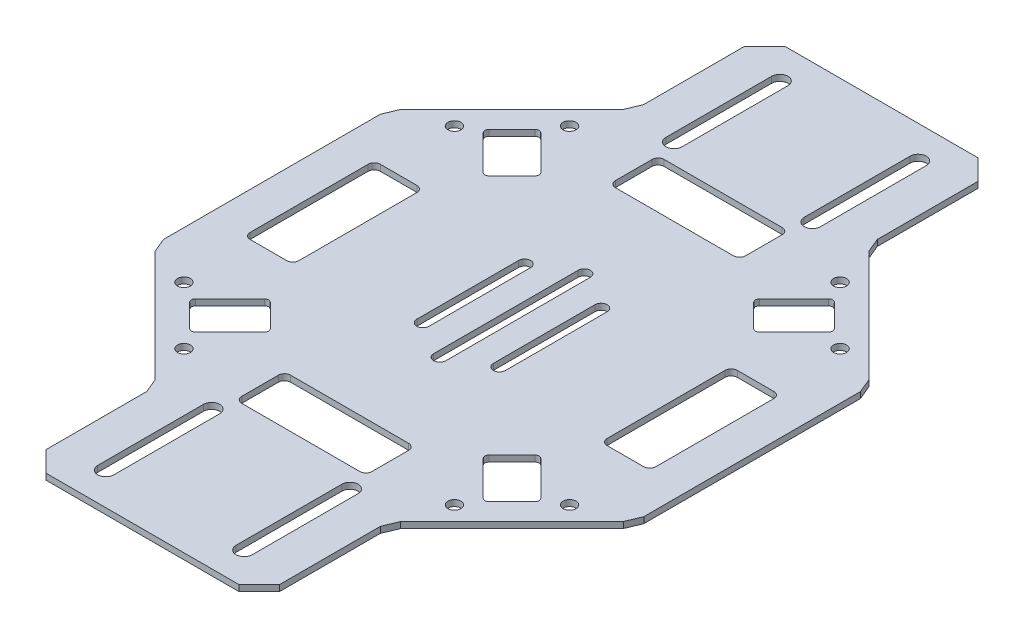
SolidWorks part; units mm, degrees
ref_plane "Front Plane" through (0, 0, 0) normal (0, 0, 1) x (1, 0, 0)
ref_plane "Top Plane" through (0, 0, 0) normal (0, 1, 0) x (1, 0, 0)
ref_plane "Right Plane" through (0, 0, 0) normal (1, 0, 0) x (0, 0, -1)
sketch "Sketch1" plane through (0, 0, 0) normal (0, -1, 0) x (1, 0, 0)
  line L0 (-19, -82.8) -> (-19, -56.8)
  line L1 (-15, -56.8) -> (-15, -82.8)
  line L2 (19, 82.8) -> (19, 56.8)
  line L3 (15, 56.8) -> (15, 82.8)
  line L4 (-15, 82.8) -> (-15, 56.8)
  line L5 (-19, 56.8) -> (-19, 82.8)
  line L6 (-14.5, 51.9) -> (14.5, 51.9)
  line L7 (16, 50.4) -> (16, 41.4)
  line L8 (14.5, 39.9) -> (-14.5, 39.9)
  line L9 (-16, 41.4) -> (-16, 50.4)
  line L10 (16, -41.4) -> (16, -50.4)
  line L11 (14.5, -51.9) -> (-14.5, -51.9)
  line L12 (-16, -50.4) -> (-16, -41.4)
  line L13 (-14.5, -39.9) -> (14.5, -39.9)
  line L14 (19, -56.8) -> (19, -82.8)
  line L15 (15, -82.8) -> (15, -56.8)
  line L16 (-10.9, -12.5) -> (-10.9, 12.5)
  line L17 (-7.9, 12.5) -> (-7.9, -12.5)
  line L18 (10.9, 12.5) -> (10.9, -12.5)
  line L19 (7.9, -12.5) -> (7.9, 12.5)
  line L20 (-32.5269, -26.8701) -> (-26.8701, -32.5269)
  line L21 (-26.8701, -33.9411) -> (-35.3553, -42.4264)
  line L22 (-36.7696, -42.4264) -> (-42.4264, -36.7696)
  line L23 (-42.4264, -35.3553) -> (-33.9411, -26.8701)
  line L24 (-26.8701, 32.5269) -> (-32.5269, 26.8701)
  line L25 (-33.9411, 26.8701) -> (-42.4264, 35.3553)
  line L26 (-42.4264, 36.7696) -> (-36.7696, 42.4264)
  line L27 (-35.3553, 42.4264) -> (-26.8701, 33.9411)
  line L28 (48.35, -16) -> (39.35, -16)
  line L29 (37.85, -14.5) -> (37.85, 14.5)
  line L30 (39.35, 16) -> (48.35, 16)
  line L31 (49.85, 14.5) -> (49.85, -14.5)
  line L32 (-39.35, -16) -> (-48.35, -16)
  line L33 (-49.85, -14.5) -> (-49.85, 14.5)
  line L34 (-48.35, 16) -> (-39.35, 16)
  line L35 (-37.85, 14.5) -> (-37.85, -14.5)
  line L36 (26.8701, -32.5269) -> (32.5269, -26.8701)
  line L37 (33.9411, -26.8701) -> (42.4264, -35.3553)
  line L38 (42.4264, -36.7696) -> (36.7696, -42.4264)
  line L39 (35.3553, -42.4264) -> (26.8701, -33.9411)
  line L40 (32.5269, 26.8701) -> (26.8701, 32.5269)
  line L41 (26.8701, 33.9411) -> (35.3553, 42.4264)
  line L42 (36.7696, 42.4264) -> (42.4264, 36.7696)
  line L43 (42.4264, 35.3553) -> (33.9411, 26.8701)
  line L44 (1.5, 17.75) -> (1.5, -17.75)
  line L45 (-1.5, -17.75) -> (-1.5, 17.75)
  line L46 (-59, 26.6102) -> (-59, -26.6102)
  line L47 (-59, -26.6102) -> (-57.5355, -30.1457)
  line L48 (-57.5355, -30.1457) -> (-30.1645, -57.5168)
  line L49 (-30.1645, -57.5168) -> (-28.7, -61.0523)
  line L50 (-28.7, -61.0523) -> (-28.7, -85.8)
  line L51 (-28.7, -85.8) -> (-23.7, -90.8)
  line L52 (-23.7, -90.8) -> (23.7, -90.8)
  line L53 (23.7, -90.8) -> (28.7, -85.8)
  line L54 (28.7, -85.8) -> (28.7, -61.0523)
  line L55 (28.7, -61.0523) -> (30.1645, -57.5168)
  line L56 (30.1645, -57.5168) -> (57.5355, -30.1457)
  line L57 (57.5355, -30.1457) -> (59, -26.6102)
  line L58 (59, -26.6102) -> (59, 26.6102)
  line L59 (59, 26.6102) -> (57.5355, 30.1457)
  line L60 (57.5355, 30.1457) -> (30.1645, 57.5168)
  line L61 (30.1645, 57.5168) -> (28.7, 61.0523)
  line L62 (28.7, 61.0523) -> (28.7, 85.8)
  line L63 (28.7, 85.8) -> (23.7, 90.8)
  line L64 (23.7, 90.8) -> (-23.7, 90.8)
  line L65 (-23.7, 90.8) -> (-28.7, 85.8)
  line L66 (-28.7, 85.8) -> (-28.7, 61.0523)
  line L67 (-28.7, 61.0523) -> (-30.1645, 57.5168)
  line L68 (-30.1645, 57.5168) -> (-57.5355, 30.1457)
  line L69 (-57.5355, 30.1457) -> (-59, 26.6102)
  line L70 (33.234, 47.3762) -> (47.3762, 33.234) construction
  arc A0 (-15, -82.8) -> (-19, -82.8) centre (-17, -82.8) cw
  arc A1 (-19, -56.8) -> (-15, -56.8) centre (-17, -56.8) cw
  arc A2 (15, 82.8) -> (19, 82.8) centre (17, 82.8) cw
  arc A3 (19, 56.8) -> (15, 56.8) centre (17, 56.8) cw
  arc A4 (-19, 82.8) -> (-15, 82.8) centre (-17, 82.8) cw
  arc A5 (-15, 56.8) -> (-19, 56.8) centre (-17, 56.8) cw
  arc A6 (-16, 50.4) -> (-14.5, 51.9) centre (-14.5, 50.4) cw
  arc A7 (14.5, 51.9) -> (16, 50.4) centre (14.5, 50.4) cw
  arc A8 (16, 41.4) -> (14.5, 39.9) centre (14.5, 41.4) cw
  arc A9 (-14.5, 39.9) -> (-16, 41.4) centre (-14.5, 41.4) cw
  arc A10 (14.5, -39.9) -> (16, -41.4) centre (14.5, -41.4) cw
  arc A11 (16, -50.4) -> (14.5, -51.9) centre (14.5, -50.4) cw
  arc A12 (-14.5, -51.9) -> (-16, -50.4) centre (-14.5, -50.4) cw
  arc A13 (-16, -41.4) -> (-14.5, -39.9) centre (-14.5, -41.4) cw
  arc A14 (15, -56.8) -> (19, -56.8) centre (17, -56.8) cw
  arc A15 (19, -82.8) -> (15, -82.8) centre (17, -82.8) cw
  arc A16 (-7.9, -12.5) -> (-10.9, -12.5) centre (-9.4, -12.5) cw
  arc A17 (-10.9, 12.5) -> (-7.9, 12.5) centre (-9.4, 12.5) cw
  arc A18 (7.9, 12.5) -> (10.9, 12.5) centre (9.4, 12.5) cw
  arc A19 (10.9, -12.5) -> (7.9, -12.5) centre (9.4, -12.5) cw
  arc A20 (-33.9411, -26.8701) -> (-32.5269, -26.8701) centre (-33.234, -27.5772) cw
  arc A21 (-26.8701, -32.5269) -> (-26.8701, -33.9411) centre (-27.5772, -33.234) cw
  arc A22 (-35.3553, -42.4264) -> (-36.7696, -42.4264) centre (-36.0624, -41.7193) cw
  arc A23 (-42.4264, -36.7696) -> (-42.4264, -35.3553) centre (-41.7193, -36.0624) cw
  arc A24 (-26.8701, 33.9411) -> (-26.8701, 32.5269) centre (-27.5772, 33.234) cw
  arc A25 (-32.5269, 26.8701) -> (-33.9411, 26.8701) centre (-33.234, 27.5772) cw
  arc A26 (-42.4264, 35.3553) -> (-42.4264, 36.7696) centre (-41.7193, 36.0624) cw
  arc A27 (-36.7696, 42.4264) -> (-35.3553, 42.4264) centre (-36.0624, 41.7193) cw
  arc A28 (49.85, -14.5) -> (48.35, -16) centre (48.35, -14.5) cw
  arc A29 (39.35, -16) -> (37.85, -14.5) centre (39.35, -14.5) cw
  arc A30 (37.85, 14.5) -> (39.35, 16) centre (39.35, 14.5) cw
  arc A31 (48.35, 16) -> (49.85, 14.5) centre (48.35, 14.5) cw
  arc A32 (-37.85, -14.5) -> (-39.35, -16) centre (-39.35, -14.5) cw
  arc A33 (-48.35, -16) -> (-49.85, -14.5) centre (-48.35, -14.5) cw
  arc A34 (-49.85, 14.5) -> (-48.35, 16) centre (-48.35, 14.5) cw
  arc A35 (-39.35, 16) -> (-37.85, 14.5) centre (-39.35, 14.5) cw
  arc A36 (26.8701, -33.9411) -> (26.8701, -32.5269) centre (27.5772, -33.234) cw
  arc A37 (32.5269, -26.8701) -> (33.9411, -26.8701) centre (33.234, -27.5772) cw
  arc A38 (42.4264, -35.3553) -> (42.4264, -36.7696) centre (41.7193, -36.0624) cw
  arc A39 (36.7696, -42.4264) -> (35.3553, -42.4264) centre (36.0624, -41.7193) cw
  arc A40 (33.9411, 26.8701) -> (32.5269, 26.8701) centre (33.234, 27.5772) cw
  arc A41 (26.8701, 32.5269) -> (26.8701, 33.9411) centre (27.5772, 33.234) cw
  arc A42 (35.3553, 42.4264) -> (36.7696, 42.4264) centre (36.0624, 41.7193) cw
  arc A43 (42.4264, 36.7696) -> (42.4264, 35.3553) centre (41.7193, 36.0624) cw
  arc A44 (-1.5, 17.75) -> (1.5, 17.75) centre (0, 17.75) cw
  arc A45 (1.5, -17.75) -> (-1.5, -17.75) centre (0, -17.75) cw
  circle A46 centre (-33.234, -47.3762) radius 1.6
  circle A47 centre (-47.3762, -33.234) radius 1.6
  circle A48 centre (-47.3762, 33.234) radius 1.6
  circle A49 centre (-33.234, 47.3762) radius 1.6
  circle A50 centre (33.234, 47.3762) radius 1.6
  circle A51 centre (47.3762, 33.234) radius 1.6
  circle A52 centre (47.3762, -33.234) radius 1.6
  circle A53 centre (33.234, -47.3762) radius 1.6
  point P178 (40.3051, 40.3051)
extrude "Boss-Extrude1" add sketch "Sketch1" against normal mid plane 1.5
sketch "Sketch2" plane through (0, 0.75, 0) normal (0, 1, 0) x (1, 0, 0)
  line L0 (33.234, -47.3762) -> (47.3762, -33.234) construction
  line L1 (33.234, -47.3762) -> (47.3762, -33.234) construction
  point P0 (40.3051, -40.3051)
sketch "Sketch3" plane through (0, -0.75, 0) normal (0, -1, 0) x (1, 0, 0)
  line L0 (33.234, 47.3762) -> (47.3762, 33.234) construction
  line L1 (33.234, 47.3762) -> (47.3762, 33.234) construction
  point P0 (40.3051, 40.3051)
  point P4 (40.3051, 40.3051)
